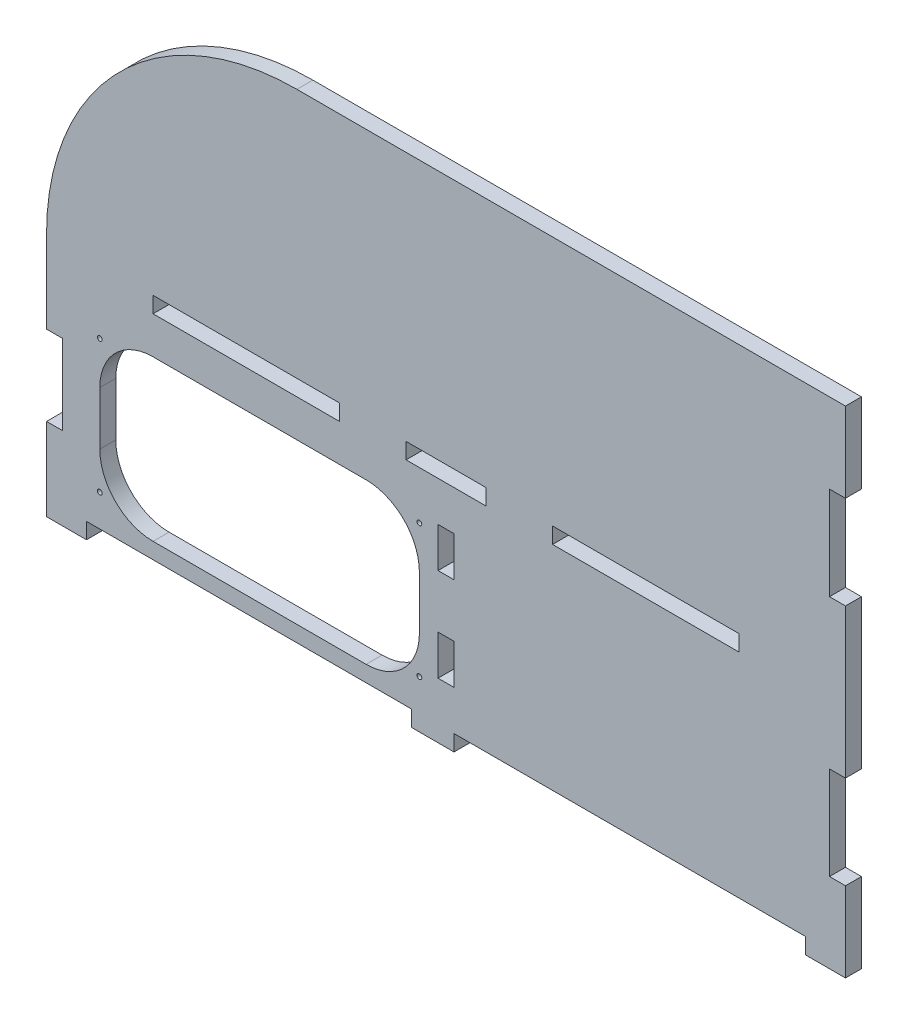
SolidWorks part; units mm, degrees
material "Acrylic (Medium-high impact)"
ref_plane "Front Plane" through (0, 0, 0) normal (0, 0, 1) x (1, 0, 0)
ref_plane "Top Plane" through (0, 0, 0) normal (0, 1, 0) x (1, 0, 0)
ref_plane "Right Plane" through (0, 0, 0) normal (1, 0, 0) x (0, 0, -1)
sketch "Sketch1" plane through (0, 0, 0) normal (0, 0, 1) x (1, 0, 0)
  line L1 (150, 93) -> (-150, 93)
  line L2 (150, 93) -> (150, -93)
  line L3 (150, -93) -> (-150, -93)
  line L4 (-150, 93) -> (-150, -93)
  line L5 (150, 93) -> (-150, -93) construction
  line L6 (150, -93) -> (-150, 93) construction
  point P0 (0, 0)
  dimension "D1" = 300
  dimension "D2" = 186
extrude "Boss-Extrude1" add sketch "Sketch1" along normal blind 6
fillet "Fillet1" radius 94 1 edges at (-150, 93, 3)
sketch "Sketch2" plane through (0, 0, 0) normal (0, 0, -1) x (-1, 0, 0)
  line L0 (150, -93) -> (-150, -93) construction
  line L1 (110, -81) -> (30, -81)
  line L2 (130, -61) -> (130, -41)
  line L3 (110, -21) -> (30, -21)
  line L4 (10, -61) -> (10, -41)
  line L5 (150, -1) -> (150, -93) construction
  arc A0 (110, -81) -> (130, -61) centre (110, -61) ccw
  arc A1 (130, -41) -> (110, -21) centre (110, -41) ccw
  arc A2 (30, -21) -> (10, -41) centre (30, -41) ccw
  arc A3 (30, -81) -> (10, -61) centre (30, -61) cw
  point P12 (130, -21)
  point P15 (10, -21)
  point P18 (10, -81)
  dimension "D5" = 20
  dimension "D1" = 12
  dimension "D2" = 20
  dimension "D3" = 120
  dimension "D4" = 60
extrude "Cut-Extrude1" cut sketch "Sketch2" against normal blind 10
sketch "Sketch3" plane through (0, 0, 6) normal (0, 0, 1) x (1, 0, 0)
  line L4 (-110, -7) -> (-40, -7)
  line L5 (-40, -7) -> (-40, -1)
  line L6 (-40, -1) -> (-110, -1)
  line L7 (-110, -1) -> (-110, -7)
  line L8 (-110, -7) -> (-40, -7)
  line L9 (-40, -7) -> (-40, -1)
  line L10 (-40, -1) -> (-110, -1)
  line L11 (-110, -1) -> (-110, -7)
  line L12 (-144, -62) -> (-144, -32)
  line L13 (-144, -32) -> (-150, -32)
  line L14 (-150, -32) -> (-150, -62)
  line L15 (-150, -62) -> (-144, -62)
  line L16 (-144, -62) -> (-144, -32)
  line L17 (-144, -32) -> (-150, -32)
  line L18 (-150, -32) -> (-150, -62)
  line L19 (-150, -62) -> (-144, -62)
  line L20 (-135, -93) -> (-13, -93)
  line L21 (-13, -93) -> (-13, -87)
  line L22 (-13, -87) -> (-135, -87)
  line L23 (-135, -87) -> (-135, -93)
  line L24 (-135, -93) -> (-13, -93)
  line L25 (-13, -93) -> (-13, -87)
  line L26 (-13, -87) -> (-135, -87)
  line L27 (-135, -87) -> (-135, -93)
  line L28 (144, 63) -> (144, 28)
  line L29 (144, 28) -> (150, 28)
  line L30 (150, 28) -> (150, 63)
  line L31 (150, 63) -> (144, 63)
  line L32 (144, 63) -> (144, 28)
  line L33 (144, 28) -> (150, 28)
  line L34 (150, 28) -> (150, 63)
  line L35 (150, 63) -> (144, 63)
  line L36 (144, -28) -> (144, -63)
  line L37 (144, -63) -> (150, -63)
  line L38 (150, -63) -> (150, -28)
  line L39 (150, -28) -> (144, -28)
  line L40 (144, -28) -> (144, -63)
  line L41 (144, -63) -> (150, -63)
  line L42 (150, -63) -> (150, -28)
  line L43 (150, -28) -> (144, -28)
  line L44 (110, -1) -> (40, -1)
  line L45 (40, -1) -> (40, -7)
  line L46 (40, -7) -> (110, -7)
  line L47 (110, -7) -> (110, -1)
  line L48 (110, -1) -> (40, -1)
  line L49 (40, -1) -> (40, -7)
  line L50 (40, -7) -> (110, -7)
  line L51 (110, -7) -> (110, -1)
  line L52 (-15, -7) -> (15, -7)
  line L53 (15, -7) -> (15, -1)
  line L54 (15, -1) -> (-15, -1)
  line L55 (-15, -1) -> (-15, -7)
  line L56 (-15, -7) -> (15, -7)
  line L57 (15, -7) -> (15, -1)
  line L58 (15, -1) -> (-15, -1)
  line L59 (-15, -1) -> (-15, -7)
  line L60 (-3, -22) -> (-3, -37)
  line L61 (-3, -37) -> (3, -37)
  line L62 (3, -37) -> (3, -22)
  line L63 (3, -22) -> (-3, -22)
  line L64 (-3, -22) -> (-3, -37)
  line L65 (-3, -37) -> (3, -37)
  line L66 (3, -37) -> (3, -22)
  line L67 (3, -22) -> (-3, -22)
  line L68 (3, -72) -> (3, -57)
  line L69 (3, -57) -> (-3, -57)
  line L70 (-3, -57) -> (-3, -72)
  line L71 (-3, -72) -> (3, -72)
  line L72 (3, -72) -> (3, -57)
  line L73 (3, -57) -> (-3, -57)
  line L74 (-3, -57) -> (-3, -72)
  line L75 (-3, -72) -> (3, -72)
  line L76 (3, -93) -> (135, -93)
  line L77 (135, -93) -> (135, -87)
  line L78 (135, -87) -> (3, -87)
  line L79 (3, -87) -> (3, -93)
  line L80 (3, -93) -> (135, -93)
  line L81 (135, -93) -> (135, -87)
  line L82 (135, -87) -> (3, -87)
  line L83 (3, -87) -> (3, -93)
  dimension "D1" = 0
  dimension "D2" = 0
  dimension "D3" = 0
  dimension "D4" = 0
  dimension "D5" = 0
  dimension "D6" = 0
  dimension "D7" = 0
  dimension "D8" = 0
  dimension "D9" = 0
  dimension "D10" = 0
extrude "Cut-Extrude2" cut sketch "Sketch3" against normal blind 6
sketch "Sketch4" plane through (0, 0, 0) normal (0, 0, -1) x (-1, 0, 0)
  circle A0 centre (130, -75) radius 0.9
  circle A1 centre (130, -25) radius 0.9
  circle A2 centre (10, -75) radius 0.9
  circle A3 centre (10, -25) radius 0.9
  dimension "D1" = 1.8
extrude "Cut-Extrude3" cut sketch "Sketch4" against normal blind 6
